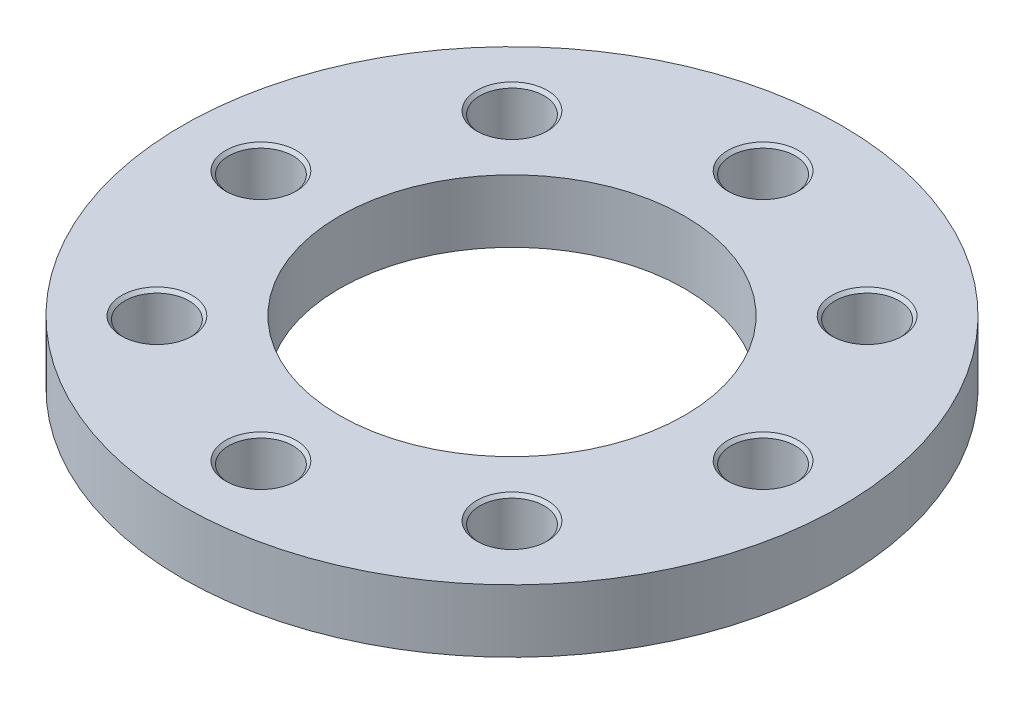
SolidWorks part; units mm, degrees
ref_plane "Front Plane" through (0, 0, 0) normal (0, 0, 1) x (1, 0, 0)
ref_plane "Top Plane" through (0, 0, 0) normal (0, 1, 0) x (1, 0, 0)
ref_plane "Right Plane" through (0, 0, 0) normal (1, 0, 0) x (0, 0, -1)
sketch "Sketch1" plane through (0, 0, 0) normal (0, 1, 0) x (1, 0, 0)
  circle A0 centre (0, 0) radius 16
  circle A1 centre (0, 0) radius 21
  circle A2 centre (0, 0) radius 11
  dimension "D1" = 32
  dimension "D2" = 5
  dimension "D3" = 5
extrude "Boss-Extrude1" add sketch "Sketch1" along normal blind 4 contours A0 A2 | A1 A0
sketch "Sketch2" plane through (0, 4, 0) normal (0, 1, 0) x (1, 0, 0)
  circle A0 centre (16, 0) radius 2.05
  dimension "D1" = 4.1
  dimension "D2" = 16
extrude "Cut-Extrude1" cut sketch "Sketch2" against normal through all contours A0
chamfer "Chamfer1" distance 0.2 angle 45 2 edges at (16, 0, 2.05) (16, 4, 2.05)
pattern_circular "CirPattern1" count 8 over 360 about axis through (0, 0, 0) along (0, 1, 0) of "Cut-Extrude1", "Chamfer1"
